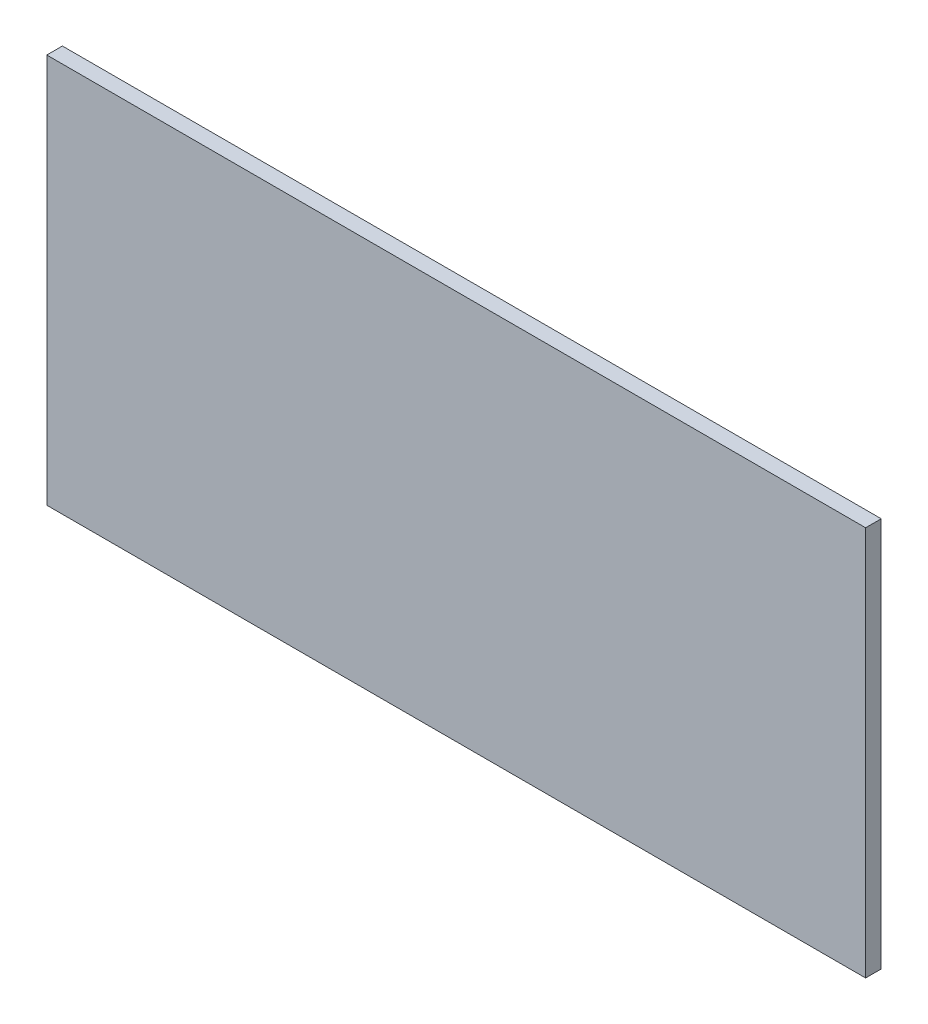
SolidWorks part; units mm, degrees
ref_plane "前视基准面" through (0, 0, 0) normal (0, 0, 1) x (1, 0, 0)
ref_plane "上视基准面" through (0, 0, 0) normal (0, 1, 0) x (1, 0, 0)
ref_plane "右视基准面" through (0, 0, 0) normal (1, 0, 0) x (0, 0, -1)
sketch "草图1" plane through (0, 0, 0) normal (0, 0, 1) x (1, 0, 0)
  line L0 (20, 25) -> (20, -25)
  line L1 (20, 25) -> (125, 25)
  line L2 (20, -25) -> (125, -25)
  line L3 (125, 25) -> (125, -25)
extrude "凸台-拉伸1" add sketch "草图1" along normal blind 2
